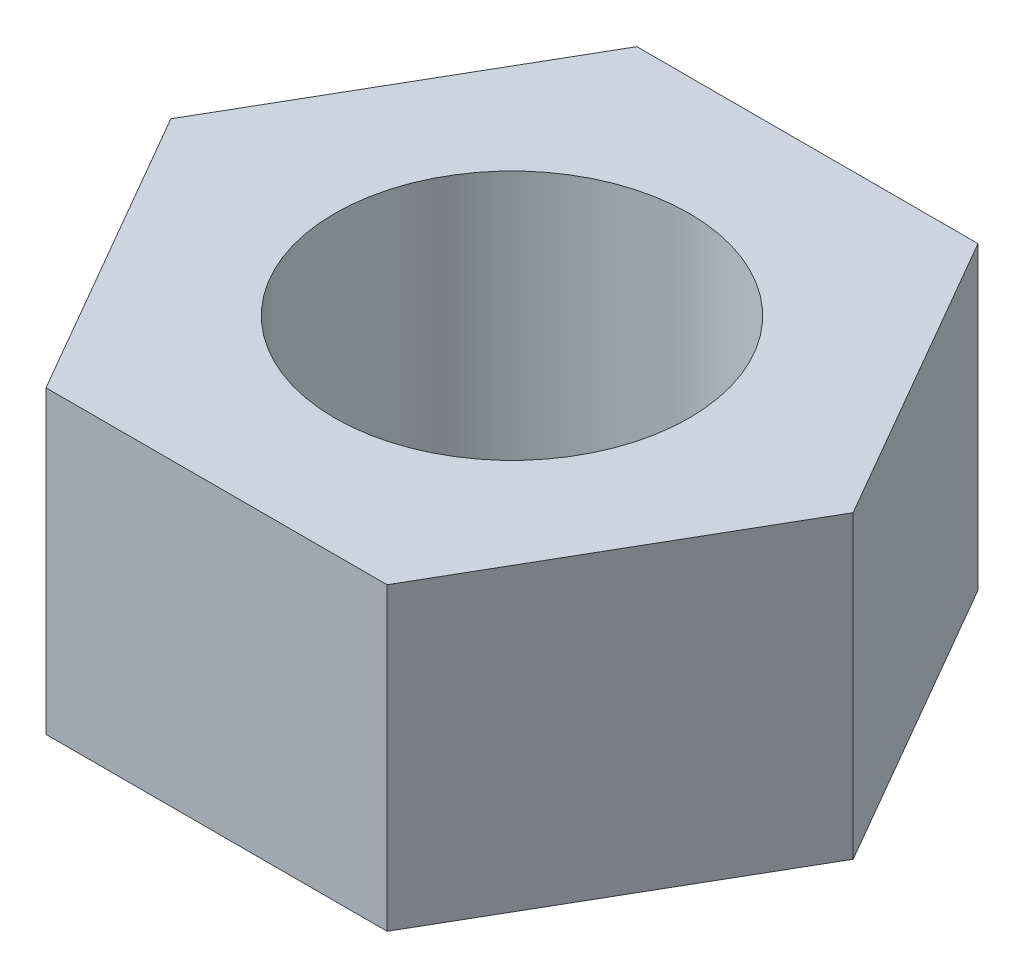
SolidWorks part; units mm, degrees
ref_plane "Front Plane" through (0, 0, 0) normal (0, 0, 1) x (1, 0, 0)
ref_plane "Top Plane" through (0, 0, 0) normal (0, 1, 0) x (1, 0, 0)
ref_plane "Right Plane" through (0, 0, 0) normal (1, 0, 0) x (0, 0, -1)
sketch "Sketch1" plane through (0, 0, 0) normal (0, 1, 0) x (1, 0, 0)
  line L0 (0, 0) -> (0, 5) construction
  line L1 (2.8867, 5) -> (-2.8867, 5)
  line L2 (-2.8867, 5) -> (-5.7735, 0)
  line L3 (-5.7735, 0) -> (-2.8867, -5)
  line L4 (-2.8867, -5) -> (2.8867, -5)
  line L5 (2.8867, -5) -> (5.7735, 0)
  line L6 (5.7735, 0) -> (2.8867, 5)
  circle A0 centre (0, 0) radius 5 construction
  point P1 (0, 0)
  point P11 (0, 10)
  dimension "D1" = 5
extrude "Boss-Extrude1" add sketch "Sketch1" along normal blind 5.08
sketch "Sketch2" plane through (0, 5.08, 0) normal (0, 1, 0) x (1, 0, 0)
  circle A0 centre (0, 0) radius 3
  dimension "D1" = 6
extrude "Cut-Extrude1" cut sketch "Sketch2" against normal through all
